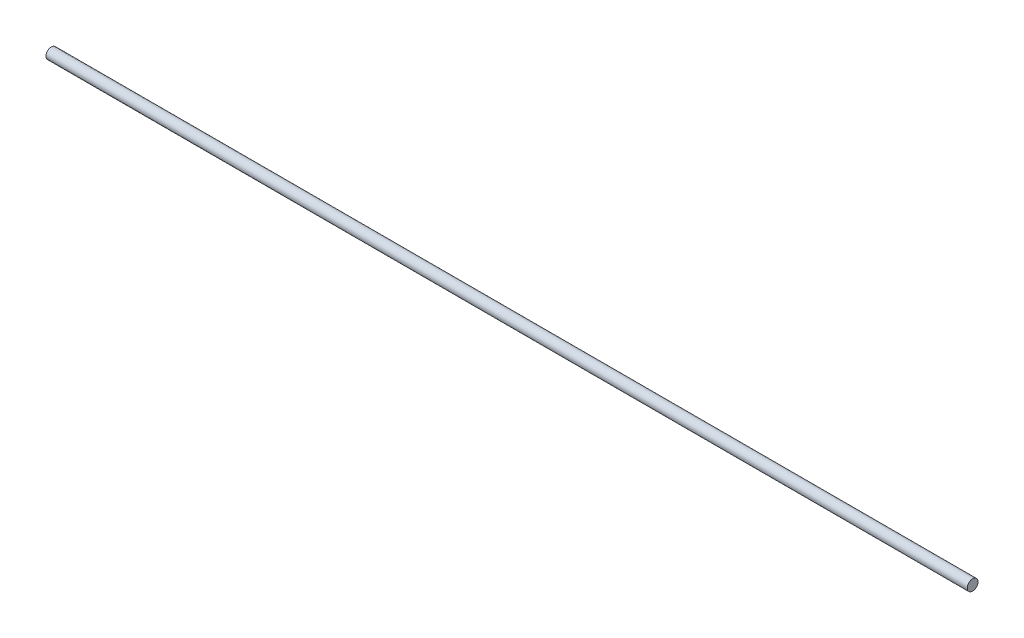
SolidWorks part; units mm, degrees
ref_plane "Front Plane" through (0, 0, 0) normal (0, 0, 1) x (1, 0, 0)
ref_plane "Top Plane" through (0, 0, 0) normal (0, 1, 0) x (1, 0, 0)
ref_plane "Right Plane" through (0, 0, 0) normal (1, 0, 0) x (0, 0, -1)
sketch "Sketch1" plane through (0, 0, 0) normal (1, 0, 0) x (0, 0, -1)
  circle A0 centre (0, 0) radius 0.875
extrude "Boss-Extrude1" add sketch "Sketch1" along normal blind 150
